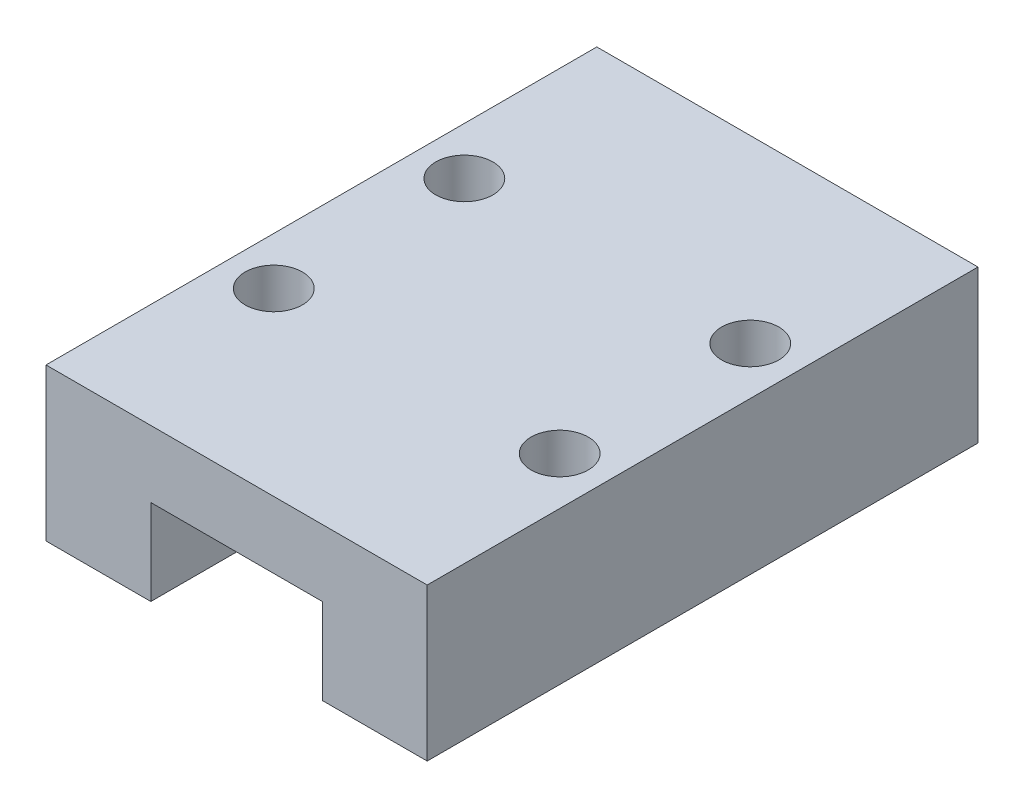
SolidWorks part; units mm, degrees
ref_plane "前视基准面" through (0, 0, 0) normal (0, 0, 1) x (1, 0, 0)
ref_plane "上视基准面" through (0, 0, 0) normal (0, 1, 0) x (1, 0, 0)
ref_plane "右视基准面" through (0, 0, 0) normal (1, 0, 0) x (0, 0, -1)
sketch "草图2" plane through (0, 0, 0) normal (0, 0, 1) x (1, 0, 0)
  line L1 (10, -4) -> (-10, -4)
  line L2 (10, -4) -> (10, 4)
  line L3 (10, 4) -> (-10, 4)
  line L4 (-10, -4) -> (-10, 4)
  line L5 (10, -4) -> (-10, 4) construction
  line L6 (10, 4) -> (-10, -4) construction
  line L7 (-4.5, 0.5) -> (4.5, 0.5)
  line L8 (-4.5, 0.5) -> (-4.5, -4)
  line L9 (-4.5, -4) -> (4.5, -4)
  line L10 (4.5, 0.5) -> (4.5, -4)
  line L11 (-4.5, 0.5) -> (4.5, -4) construction
  line L12 (-4.5, -4) -> (4.5, 0.5) construction
  point P0 (0, 0)
  point P6 (0, -1.75)
  dimension "D1" = 20
  dimension "D2" = 8
  dimension "D3" = 9
  dimension "D4" = 4.5
extrude "凸台-拉伸1" add sketch "草图2" along normal blind 28.9 contours L7 L10 L1 L2 L3 L4 L8
sketch "草图3" plane through (0, 4, 0) normal (0, 1, 0) x (1, 0, 0)
  line L0 (-10, 0) -> (10, -28.9) construction
  line L1 (-10, -28.9) -> (-10, 0) construction
  line L2 (-7.5, -19.45) -> (7.5, -19.45) construction
  line L3 (-7.5, -19.45) -> (-7.5, -9.45) construction
  line L4 (-7.5, -9.45) -> (7.5, -9.45) construction
  line L5 (7.5, -19.45) -> (7.5, -9.45) construction
  line L6 (-7.5, -19.45) -> (7.5, -9.45) construction
  line L7 (-7.5, -9.45) -> (7.5, -19.45) construction
  circle A0 centre (-7.5, -9.45) radius 1.5
  circle A1 centre (7.5, -9.45) radius 1.5
  circle A2 centre (7.5, -19.45) radius 1.5
  circle A3 centre (-7.5, -19.45) radius 1.5
  point P4 (0, -14.45)
  dimension "D3" = 3
  dimension "D4" = 3
  dimension "D5" = 3
  dimension "D6" = 3
  dimension "D1" = 10
  dimension "D2" = 2.5
extrude "切除-拉伸1" cut sketch "草图3" against normal blind 3
